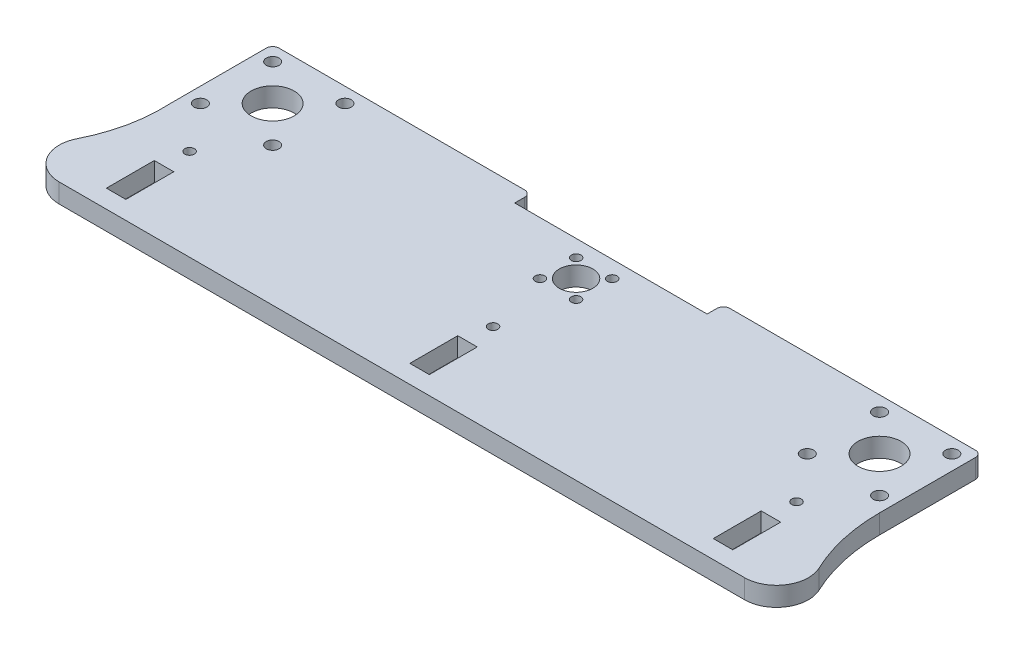
SolidWorks part; units mm, degrees
ref_plane "Alzado" through (0, 0, 0) normal (0, 0, 1) x (1, 0, 0)
ref_plane "Planta" through (0, 0, 0) normal (0, 1, 0) x (1, 0, 0)
ref_plane "Vista lateral" through (0, 0, 0) normal (1, 0, 0) x (0, 0, -1)
sketch "Croquis1" plane through (0, 0, 0) normal (0, 1, 0) x (1, 0, 0)
  line L0 (16.2827, 43.6446) -> (71.803, 43.6446)
  line L1 (-124.8326, 43.6446) -> (-103.4683, 43.6446)
  line L2 (-126.8326, 41.6446) -> (-126.8326, 11.6447)
  line L3 (-103.4683, 43.6446) -> (-60.497, 43.6446)
  line L4 (14.2827, 41.6446) -> (14.2827, 38.5546)
  line L5 (14.2827, 38.5546) -> (-45.948, 38.5546)
  line L6 (-126.8326, 27.6446) -> (-126.8326, 11.6446)
  line L7 (-126.8326, 11.6446) -> (-126.8326, 43.6446)
  line L8 (-60.497, 43.6446) -> (-47.948, 43.6446)
  line L9 (95.1674, 41.6446) -> (95.1674, 11.6447)
  line L10 (93.1674, 43.6446) -> (71.803, 43.6446)
  line L11 (-45.948, 41.6446) -> (-45.948, 38.5546)
  line L12 (-24.1326, 19.3446) -> (-7.5326, 35.9446) construction
  line L13 (-122.9609, -27.0571) -> (91.6208, -27.0571)
  line L14 (-24.1326, 35.9446) -> (-7.5326, 19.3446) construction
  line L15 (-126.8326, 43.6446) -> (-94.8326, 11.6446) construction
  line L16 (-126.8326, 11.6446) -> (-94.8326, 43.6446) construction
  line L17 (-126.8326, 11.6446) -> (-94.8326, 11.6446) construction
  line L18 (-94.8326, 11.6446) -> (95.1674, 11.6447) construction
  line L22 (-113.8826, -6.3554) -> (-107.7826, -6.3554)
  line L23 (-113.8826, -6.3554) -> (-113.8826, -21.3554)
  line L24 (-113.8826, -21.3554) -> (-107.7826, -21.3554)
  line L25 (-107.7826, -6.3554) -> (-107.7826, -21.3554)
  line L27 (76.1174, -6.3554) -> (76.1174, -21.3554)
  line L28 (82.2174, -21.3553) -> (76.1174, -21.3554)
  line L29 (82.2174, -6.3553) -> (82.2174, -21.3553)
  line L30 (82.2174, -6.3553) -> (76.1174, -6.3554)
  line L31 (-18.8826, -6.3554) -> (-18.8826, -21.3554)
  line L32 (-12.7826, -21.3553) -> (-18.8826, -21.3554)
  line L33 (-12.7826, -6.3553) -> (-12.7826, -21.3553)
  line L34 (-12.7826, -6.3553) -> (-18.8826, -6.3554)
  line L35 (79.1674, 1.6446) -> (-110.8326, 1.6446) construction
  circle A0 centre (-15.8326, 27.6446) radius 5.25
  circle A1 centre (-110.8326, 27.6446) radius 6.75
  circle A2 centre (79.1674, 27.6446) radius 6.75
  arc A3 (91.6208, -27.0571) -> (100.6583, -12.7766) centre (91.6208, -17.0571) ccw
  circle A4 centre (-99.5189, 38.9583) radius 2
  circle A5 centre (-122.1464, 38.9583) radius 2
  circle A6 centre (-99.5189, 16.3309) radius 2
  circle A7 centre (-122.1464, 16.3309) radius 2
  circle A8 centre (90.4811, 16.3309) radius 2
  circle A9 centre (67.8536, 16.3309) radius 2
  circle A10 centre (67.8536, 38.9583) radius 2
  arc A11 (-126.8326, 11.6447) -> (-131.8924, -12.5595) centre (-174.7801, 9.0369) cw
  arc A12 (95.1674, 11.6447) -> (100.6583, -12.7766) centre (152.2197, 11.6447) ccw
  arc A13 (-131.8924, -12.5595) -> (-122.9609, -27.0571) centre (-122.9609, -17.0571) ccw
  circle A14 centre (-10.1758, 33.3015) radius 1.5
  circle A15 centre (-21.4895, 33.3015) radius 1.5
  circle A16 centre (-21.4895, 21.9878) radius 1.5
  circle A17 centre (-10.1758, 21.9878) radius 1.5
  circle A18 centre (-110.8326, 1.6446) radius 1.5
  arc A20 (93.1674, 43.6446) -> (95.1674, 41.6446) centre (93.1674, 41.6446) cw
  arc A21 (-126.8326, 41.6446) -> (-124.8326, 43.6446) centre (-124.8326, 41.6446) cw
  circle A23 centre (79.1674, 1.6446) radius 1.5
  arc A24 (-47.948, 43.6446) -> (-45.948, 41.6446) centre (-47.948, 41.6446) cw
  circle A25 centre (90.4811, 38.9583) radius 2
  arc A26 (14.2827, 41.6446) -> (16.2827, 43.6446) centre (16.2827, 41.6446) cw
  circle A28 centre (-15.828, 1.6446) radius 1.5
  point P51 (-15.8326, 43.6446)
  dimension "D1" = 10.5
  dimension "D2" = 13.5
  dimension "D4" = 13.5
  dimension "D5" = 4
  dimension "D6" = 4
  dimension "D7" = 4
  dimension "D8" = 4
  dimension "D9" = 2
  dimension "D21" = 10
  dimension "D3" = 95
  dimension "D10" = 5.2532
  dimension "D11" = 5.2532
  dimension "D12" = 11.3137
  dimension "D13" = 11.3137
  dimension "D14" = 11.3137
  dimension "D15" = 11.3137
  dimension "D16" = 10
  dimension "D17" = 16
  dimension "D18" = 6.1
  dimension "D19" = 15
  dimension "D20" = 8
  dimension "D22" = 10
  dimension "D23" = 10
extrude "Saliente-Extruir1" add sketch "Croquis1" along normal blind 6 contours A26 L4 L5 L11 A24 L8 L3 L1 A21 L2 L6 A11 A13 L13 A3 A12 L9 A20 L10 L0 A25 A10 A8 A7 A6 A5 A4 A2 A1 A0 L34 L33 L32 L31 L30 L29 L28 L27
